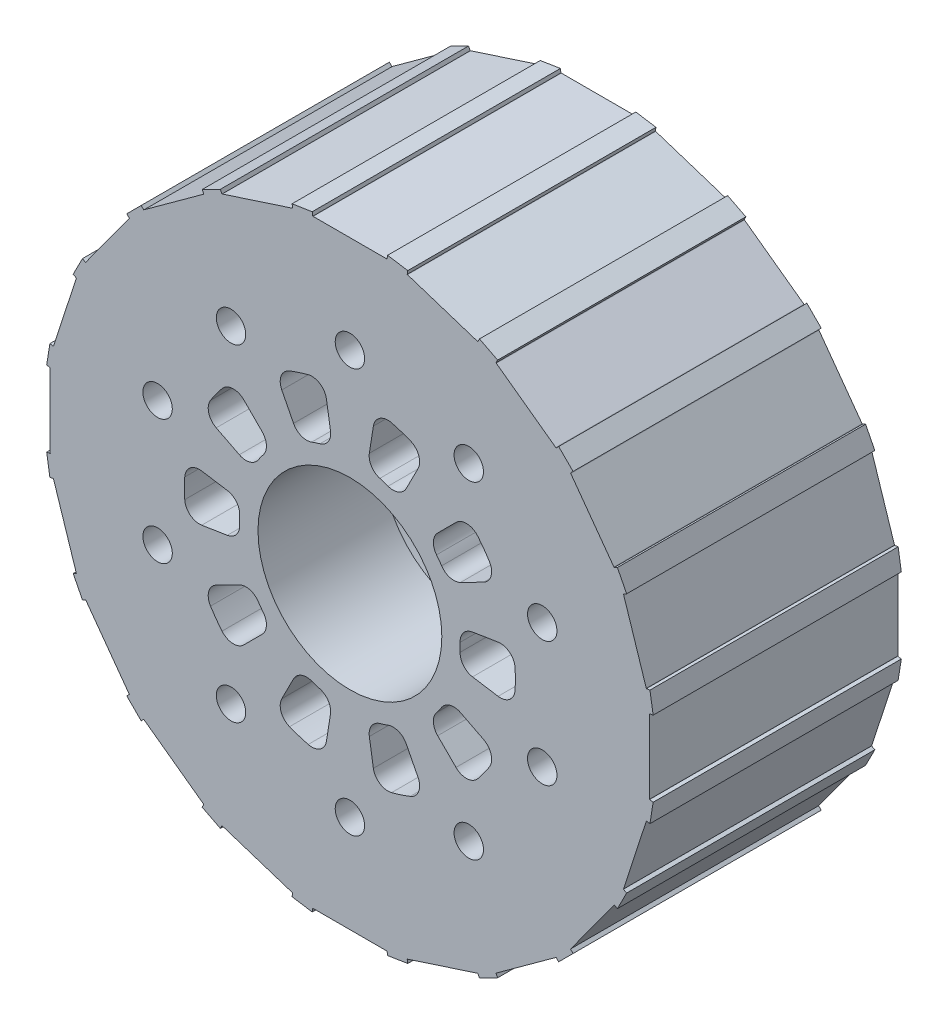
SolidWorks part; units mm, degrees
ref_plane "Ön Düzlem" through (0, 0, 0) normal (0, 0, 1) x (1, 0, 0)
ref_plane "Üst Düzlem" through (0, 0, 0) normal (0, 1, 0) x (1, 0, 0)
ref_plane "Sağ Düzlem" through (0, 0, 0) normal (1, 0, 0) x (0, 0, -1)
sketch "Sketch1" plane through (0, 0, 0) normal (0, 0, 1) x (1, 0, 0)
  line L0 (0, 0) -> (0, 81.5)
  line L1 (10, 81.5) -> (-10, 81.5)
  line L2 (-10, 81.5) -> (-10, 87.5)
  line L3 (10, 81.5) -> (10, 87.5)
  line L4 (15.6743, 80.6013) -> (17.5284, 86.3076)
  line L5 (34.6955, 74.4209) -> (36.5496, 80.1273)
  line L6 (34.6955, 74.4209) -> (15.6743, 80.6013)
  line L7 (39.8143, 71.8127) -> (43.341, 76.6668)
  line L8 (55.9947, 60.057) -> (59.5214, 64.9111)
  line L9 (55.9947, 60.057) -> (39.8143, 71.8127)
  line L10 (60.057, 55.9947) -> (64.9111, 59.5214)
  line L11 (71.8127, 39.8143) -> (76.6668, 43.341)
  line L12 (71.8127, 39.8143) -> (60.057, 55.9947)
  line L13 (74.4209, 34.6955) -> (80.1273, 36.5496)
  line L14 (80.6013, 15.6743) -> (86.3076, 17.5284)
  line L15 (80.6013, 15.6743) -> (74.4209, 34.6955)
  line L16 (81.5, 10) -> (87.5, 10)
  line L17 (81.5, -10) -> (87.5, -10)
  line L18 (81.5, -10) -> (81.5, 10)
  line L19 (80.6013, -15.6743) -> (86.3076, -17.5284)
  line L20 (74.4209, -34.6955) -> (80.1273, -36.5496)
  line L21 (74.4209, -34.6955) -> (80.6013, -15.6743)
  line L22 (71.8127, -39.8143) -> (76.6668, -43.341)
  line L23 (60.057, -55.9947) -> (64.9111, -59.5214)
  line L24 (60.057, -55.9947) -> (71.8127, -39.8143)
  line L25 (55.9947, -60.057) -> (59.5214, -64.9111)
  line L26 (39.8143, -71.8127) -> (43.341, -76.6668)
  line L27 (39.8143, -71.8127) -> (55.9947, -60.057)
  line L28 (34.6955, -74.4209) -> (36.5496, -80.1273)
  line L29 (15.6743, -80.6013) -> (17.5284, -86.3076)
  line L30 (15.6743, -80.6013) -> (34.6955, -74.4209)
  line L31 (10, -81.5) -> (10, -87.5)
  line L32 (-10, -81.5) -> (-10, -87.5)
  line L33 (-10, -81.5) -> (10, -81.5)
  line L34 (-15.6743, -80.6013) -> (-17.5284, -86.3076)
  line L35 (-34.6955, -74.4209) -> (-36.5496, -80.1273)
  line L36 (-34.6955, -74.4209) -> (-15.6743, -80.6013)
  line L37 (-39.8143, -71.8127) -> (-43.341, -76.6668)
  line L38 (-55.9947, -60.057) -> (-59.5214, -64.9111)
  line L39 (-55.9947, -60.057) -> (-39.8143, -71.8127)
  line L40 (-60.057, -55.9947) -> (-64.9111, -59.5214)
  line L41 (-71.8127, -39.8143) -> (-76.6668, -43.341)
  line L42 (-71.8127, -39.8143) -> (-60.057, -55.9947)
  line L43 (-74.4209, -34.6955) -> (-80.1273, -36.5496)
  line L44 (-80.6013, -15.6743) -> (-86.3076, -17.5284)
  line L45 (-80.6013, -15.6743) -> (-74.4209, -34.6955)
  line L46 (-81.5, -10) -> (-87.5, -10)
  line L47 (-81.5, 10) -> (-87.5, 10)
  line L48 (-81.5, 10) -> (-81.5, -10)
  line L49 (-80.6013, 15.6743) -> (-86.3076, 17.5284)
  line L50 (-74.4209, 34.6955) -> (-80.1273, 36.5496)
  line L51 (-74.4209, 34.6955) -> (-80.6013, 15.6743)
  line L52 (-71.8127, 39.8143) -> (-76.6668, 43.341)
  line L53 (-60.057, 55.9947) -> (-64.9111, 59.5214)
  line L54 (-60.057, 55.9947) -> (-71.8127, 39.8143)
  line L55 (-55.9947, 60.057) -> (-59.5214, 64.9111)
  line L56 (-39.8143, 71.8127) -> (-43.341, 76.6668)
  line L57 (-39.8143, 71.8127) -> (-55.9947, 60.057)
  line L58 (-34.6955, 74.4209) -> (-36.5496, 80.1273)
  line L59 (-15.6743, 80.6013) -> (-17.5284, 86.3076)
  line L60 (-15.6743, 80.6013) -> (-34.6955, 74.4209)
  line L61 (34.6955, 74.4209) -> (34.7846, 74.3755)
  line L62 (35.1494, 75.3119) -> (40.2683, 72.7037) construction
  line L63 (39.7252, 71.8581) -> (39.8143, 71.8127)
  line L64 (35.2385, 75.2665) -> (40.1792, 72.7491)
  line L65 (34.7846, 74.3755) -> (35.2385, 75.2665)
  line L66 (55.9947, 60.057) -> (56.0654, 59.9863)
  line L67 (39.7252, 71.8581) -> (40.1792, 72.7491)
  line L68 (34.7846, 74.3755) -> (35.1931, 75.1774) construction
  line L69 (39.7252, 71.8581) -> (40.1338, 72.66) construction
  line L70 (35.1931, 75.1774) -> (40.1338, 72.66) construction
  line L71 (34.6955, 74.4209) -> (35.1494, 75.3119) construction
  line L72 (39.8143, 71.8127) -> (40.2683, 72.7037) construction
  line L73 (56.0654, 59.9863) -> (56.7725, 60.6934)
  line L74 (56.7725, 60.6934) -> (60.6934, 56.7725)
  line L75 (59.9863, 56.0654) -> (60.6934, 56.7725)
  line L76 (59.9863, 56.0654) -> (60.057, 55.9947)
  line L77 (71.8127, 39.8143) -> (71.8581, 39.7252)
  line L78 (71.8581, 39.7252) -> (72.7491, 40.1792)
  line L79 (72.7491, 40.1792) -> (75.2665, 35.2385)
  line L80 (74.3755, 34.7846) -> (75.2665, 35.2385)
  line L81 (74.3755, 34.7846) -> (74.4209, 34.6955)
  line L82 (80.6013, 15.6743) -> (80.6169, 15.5756)
  line L83 (80.6169, 15.5756) -> (81.6046, 15.732)
  line L84 (81.6046, 15.732) -> (82.472, 10.2552)
  line L85 (81.4844, 10.0988) -> (82.472, 10.2552)
  line L86 (81.4844, 10.0988) -> (81.5, 10)
  line L87 (81.5, -10) -> (81.4844, -10.0988)
  line L88 (81.4844, -10.0988) -> (82.472, -10.2552)
  line L89 (82.472, -10.2552) -> (81.6046, -15.732)
  line L90 (80.6169, -15.5756) -> (81.6046, -15.732)
  line L91 (80.6169, -15.5756) -> (80.6013, -15.6743)
  line L92 (74.4209, -34.6955) -> (74.3755, -34.7846)
  line L93 (74.3755, -34.7846) -> (75.2665, -35.2385)
  line L94 (75.2665, -35.2385) -> (72.7491, -40.1792)
  line L95 (71.8581, -39.7252) -> (72.7491, -40.1792)
  line L96 (71.8581, -39.7252) -> (71.8127, -39.8143)
  line L97 (60.057, -55.9947) -> (59.9863, -56.0654)
  line L98 (59.9863, -56.0654) -> (60.6934, -56.7725)
  line L99 (60.6934, -56.7725) -> (56.7725, -60.6934)
  line L100 (56.0654, -59.9863) -> (56.7725, -60.6934)
  line L101 (56.0654, -59.9863) -> (55.9947, -60.057)
  line L102 (39.8143, -71.8127) -> (39.7252, -71.8581)
  line L103 (39.7252, -71.8581) -> (40.1792, -72.7491)
  line L104 (40.1792, -72.7491) -> (35.2385, -75.2665)
  line L105 (34.7846, -74.3755) -> (35.2385, -75.2665)
  line L106 (34.7846, -74.3755) -> (34.6955, -74.4209)
  line L107 (15.6743, -80.6013) -> (15.5756, -80.6169)
  line L108 (15.5756, -80.6169) -> (15.732, -81.6046)
  line L109 (15.732, -81.6046) -> (10.2552, -82.472)
  line L110 (10.0988, -81.4844) -> (10.2552, -82.472)
  line L111 (10.0988, -81.4844) -> (10, -81.5)
  line L112 (-10, -81.5) -> (-10.0988, -81.4844)
  line L113 (-10.0988, -81.4844) -> (-10.2552, -82.472)
  line L114 (-10.2552, -82.472) -> (-15.732, -81.6046)
  line L115 (-15.5756, -80.6169) -> (-15.732, -81.6046)
  line L116 (-15.5756, -80.6169) -> (-15.6743, -80.6013)
  line L117 (-34.6955, -74.4209) -> (-34.7846, -74.3755)
  line L118 (-34.7846, -74.3755) -> (-35.2385, -75.2665)
  line L119 (-35.2385, -75.2665) -> (-40.1792, -72.7491)
  line L120 (-39.7252, -71.8581) -> (-40.1792, -72.7491)
  line L121 (-39.7252, -71.8581) -> (-39.8143, -71.8127)
  line L122 (-55.9947, -60.057) -> (-56.0654, -59.9863)
  line L123 (-56.0654, -59.9863) -> (-56.7725, -60.6934)
  line L124 (-56.7725, -60.6934) -> (-60.6934, -56.7725)
  line L125 (-59.9863, -56.0654) -> (-60.6934, -56.7725)
  line L126 (-59.9863, -56.0654) -> (-60.057, -55.9947)
  line L127 (-71.8127, -39.8143) -> (-71.8581, -39.7252)
  line L128 (-71.8581, -39.7252) -> (-72.7491, -40.1792)
  line L129 (-72.7491, -40.1792) -> (-75.2665, -35.2385)
  line L130 (-74.3755, -34.7846) -> (-75.2665, -35.2385)
  line L131 (-74.3755, -34.7846) -> (-74.4209, -34.6955)
  line L132 (-80.6013, -15.6743) -> (-80.6169, -15.5756)
  line L133 (-80.6169, -15.5756) -> (-81.6046, -15.732)
  line L134 (-81.6046, -15.732) -> (-82.472, -10.2552)
  line L135 (-81.4844, -10.0988) -> (-82.472, -10.2552)
  line L136 (-81.4844, -10.0988) -> (-81.5, -10)
  line L137 (-81.5, 10) -> (-81.4844, 10.0988)
  line L138 (-81.4844, 10.0988) -> (-82.472, 10.2552)
  line L139 (-82.472, 10.2552) -> (-81.6046, 15.732)
  line L140 (-80.6169, 15.5756) -> (-81.6046, 15.732)
  line L141 (-80.6169, 15.5756) -> (-80.6013, 15.6743)
  line L142 (-74.4209, 34.6955) -> (-74.3755, 34.7846)
  line L143 (-74.3755, 34.7846) -> (-75.2665, 35.2385)
  line L144 (-75.2665, 35.2385) -> (-72.7491, 40.1792)
  line L145 (-71.8581, 39.7252) -> (-72.7491, 40.1792)
  line L146 (-71.8581, 39.7252) -> (-71.8127, 39.8143)
  line L147 (-60.057, 55.9947) -> (-59.9863, 56.0654)
  line L148 (-59.9863, 56.0654) -> (-60.6934, 56.7725)
  line L149 (-60.6934, 56.7725) -> (-56.7725, 60.6934)
  line L150 (-56.0654, 59.9863) -> (-56.7725, 60.6934)
  line L151 (-56.0654, 59.9863) -> (-55.9947, 60.057)
  line L152 (-39.8143, 71.8127) -> (-39.7252, 71.8581)
  line L153 (-39.7252, 71.8581) -> (-40.1792, 72.7491)
  line L154 (-40.1792, 72.7491) -> (-35.2385, 75.2665)
  line L155 (-34.7846, 74.3755) -> (-35.2385, 75.2665)
  line L156 (-34.7846, 74.3755) -> (-34.6955, 74.4209)
  line L157 (-15.6743, 80.6013) -> (-15.5756, 80.6169)
  line L158 (-15.5756, 80.6169) -> (-15.732, 81.6046)
  line L159 (-15.732, 81.6046) -> (-10.2552, 82.472)
  line L160 (-10.0988, 81.4844) -> (-10.2552, 82.472)
  line L161 (-10.0988, 81.4844) -> (-10, 81.5)
  line L162 (10, 81.5) -> (10.0988, 81.4844)
  line L163 (10.0988, 81.4844) -> (10.2552, 82.472)
  line L164 (10.2552, 82.472) -> (15.732, 81.6046)
  line L165 (15.5756, 80.6169) -> (15.732, 81.6046)
  line L166 (15.5756, 80.6169) -> (15.6743, 80.6013)
  circle A0 centre (0, 0) radius 25
  arc A2 (10, 87.5) -> (-10, 87.5) centre (0, 38) ccw
  arc A3 (36.5496, 80.1273) -> (17.5284, 86.3076) centre (11.7426, 36.1401) ccw
  arc A4 (59.5214, 64.9111) -> (43.341, 76.6668) centre (22.3358, 30.7426) ccw
  arc A5 (76.6668, 43.341) -> (64.9111, 59.5214) centre (30.7426, 22.3358) ccw
  arc A6 (86.3076, 17.5284) -> (80.1273, 36.5496) centre (36.1401, 11.7426) ccw
  arc A7 (87.5, -10) -> (87.5, 10) centre (38, 0) ccw
  arc A8 (80.1273, -36.5496) -> (86.3076, -17.5284) centre (36.1401, -11.7426) ccw
  arc A9 (64.9111, -59.5214) -> (76.6668, -43.341) centre (30.7426, -22.3358) ccw
  arc A10 (43.341, -76.6668) -> (59.5214, -64.9111) centre (22.3358, -30.7426) ccw
  arc A11 (17.5284, -86.3076) -> (36.5496, -80.1273) centre (11.7426, -36.1401) ccw
  arc A12 (-10, -87.5) -> (10, -87.5) centre (0, -38) ccw
  arc A13 (-36.5496, -80.1273) -> (-17.5284, -86.3076) centre (-11.7426, -36.1401) ccw
  arc A14 (-59.5214, -64.9111) -> (-43.341, -76.6668) centre (-22.3358, -30.7426) ccw
  arc A15 (-76.6668, -43.341) -> (-64.9111, -59.5214) centre (-30.7426, -22.3358) ccw
  arc A16 (-86.3076, -17.5284) -> (-80.1273, -36.5496) centre (-36.1401, -11.7426) ccw
  arc A17 (-87.5, 10) -> (-87.5, -10) centre (-38, 0) ccw
  arc A18 (-80.1273, 36.5496) -> (-86.3076, 17.5284) centre (-36.1401, 11.7426) ccw
  arc A19 (-64.9111, 59.5214) -> (-76.6668, 43.341) centre (-30.7426, 22.3358) ccw
  arc A20 (-43.341, 76.6668) -> (-59.5214, 64.9111) centre (-22.3358, 30.7426) ccw
  arc A21 (-17.5284, 86.3076) -> (-36.5496, 80.1273) centre (-11.7426, 36.1401) ccw
  point P7 (0, 81.5)
  point P107 (0, 0)
  point P231 (0, 0)
  dimension "D1" = 81.5
  dimension "D3" = 50.5
  dimension "D8" = 50
  dimension "D2" = 20
  dimension "D4" = 6
  dimension "D5" = 6
  dimension "D7" = 20
  dimension "D6" = 20
extrude "Boss-Extrude1" add sketch "Sketch1" along normal blind 67.5
sketch "Sketch2" plane through (0, 0, 0) normal (0, 0, -1) x (-1, 0, 0)
  circle A0 centre (0, 0) radius 68
extrude "Cut-Extrude1" cut sketch "Sketch2" against normal blind 33.75
sketch "Sketch3" plane through (0, 0, 33.75) normal (0, 0, -1) x (-1, 0, 0)
  line L0 (0, 0) -> (0, 55)
  circle A0 centre (0, 55) radius 4
  circle A1 centre (32.3282, 44.4959) radius 4
  circle A2 centre (52.3081, 16.9959) radius 4
  circle A3 centre (52.3081, -16.9959) radius 4
  circle A4 centre (32.3282, -44.4959) radius 4
  circle A5 centre (0, -55) radius 4
  circle A6 centre (-32.3282, -44.4959) radius 4
  circle A7 centre (-52.3081, -16.9959) radius 4
  circle A8 centre (-52.3081, 16.9959) radius 4
  circle A9 centre (-32.3282, 44.4959) radius 4
  point P5 (0, 0)
  point P24 (0, 0)
  dimension "D1" = 10
extrude "Cut-Extrude2" cut sketch "Sketch3" against normal blind 33.75 contours A0 | A9 | A8 | A1 | A2 | A3 | A4 | A5 | A6 | A7
sketch "Sketch4" plane through (0, 0, 33.75) normal (0, 0, -1) x (-1, 0, 0)
  line L1 (-5.2818, 33.3482) -> (-6.3832, 40.302)
  line L2 (-15.3285, 30.0838) -> (-18.5248, 36.357)
  line L3 (15.3285, 30.0838) -> (18.5248, 36.357)
  line L4 (5.2818, 33.3482) -> (6.3832, 40.302)
  line L5 (30.0838, 15.3285) -> (36.357, 18.5248)
  line L6 (23.8747, 23.8747) -> (28.8531, 28.8531)
  line L7 (33.3482, -5.2818) -> (40.302, -6.3832)
  line L8 (33.3482, 5.2818) -> (40.302, 6.3832)
  line L9 (23.8747, -23.8747) -> (28.8531, -28.8531)
  line L10 (30.0838, -15.3285) -> (36.357, -18.5248)
  line L11 (5.2818, -33.3482) -> (6.3832, -40.302)
  line L12 (15.3285, -30.0838) -> (18.5248, -36.357)
  line L13 (-15.3285, -30.0838) -> (-18.5248, -36.357)
  line L14 (-5.2818, -33.3482) -> (-6.3832, -40.302)
  line L18 (-30.0838, 15.3285) -> (-36.357, 18.5248)
  line L19 (-23.8747, 23.8747) -> (-28.8531, 28.8531)
  line L24 (-30.0838, -15.3285) -> (-36.357, -18.5248)
  line L25 (-23.8747, -23.8747) -> (-28.8531, -28.8531)
  line L26 (-33.3482, 5.2818) -> (-40.302, 6.3832)
  line L27 (-33.3482, -5.2818) -> (-40.302, -6.3832)
  arc A0 (-34.7724, 28.5636) -> (-37.9109, 24.2439) centre (0, 0) ccw
  arc A1 (-23.5616, 18.5702) -> (-24.9422, 16.6699) centre (0, 0) ccw
  arc A6 (-37.9109, 24.2439) -> (-36.357, 18.5248) centre (-34.541, 22.0888) ccw
  arc A7 (-30.0838, 15.3285) -> (-24.9422, 16.6699) centre (-28.2679, 18.8925) ccw
  arc A8 (-23.5616, 18.5702) -> (-23.8747, 23.8747) centre (-26.7031, 21.0462) ccw
  arc A9 (-28.8531, 28.8531) -> (-34.7724, 28.5636) centre (-31.6815, 26.0246) ccw
  arc A10 (-6.3832, 40.302) -> (-11.3422, 43.5472) centre (-10.334, 39.6763) ccw
  arc A11 (-8.1464, 28.8728) -> (-5.2818, 33.3482) centre (-9.2326, 32.7225) ccw
  arc A12 (-11.3422, 43.5472) -> (-16.4204, 41.8971) centre (0, 0) ccw
  arc A13 (-16.4204, 41.8971) -> (-18.5248, 36.357) centre (-14.9608, 38.173) ccw
  arc A14 (-15.3285, 30.0838) -> (-10.3804, 28.1469) centre (-11.7645, 31.8998) ccw
  arc A15 (-8.1464, 28.8728) -> (-10.3804, 28.1469) centre (0, 0) ccw
  arc A16 (18.5248, 36.357) -> (16.4204, 41.8971) centre (14.9608, 38.173) ccw
  arc A17 (10.3804, 28.1469) -> (15.3285, 30.0838) centre (11.7645, 31.8998) ccw
  arc A18 (16.4204, 41.8971) -> (11.3422, 43.5472) centre (0, 0) ccw
  arc A19 (11.3422, 43.5472) -> (6.3832, 40.302) centre (10.334, 39.6763) ccw
  arc A20 (5.2818, 33.3482) -> (8.1464, 28.8728) centre (9.2326, 32.7225) ccw
  arc A21 (10.3804, 28.1469) -> (8.1464, 28.8728) centre (0, 0) ccw
  arc A22 (36.357, 18.5248) -> (37.9109, 24.2439) centre (34.541, 22.0888) ccw
  arc A23 (24.9422, 16.6699) -> (30.0838, 15.3285) centre (28.2679, 18.8925) ccw
  arc A24 (37.9109, 24.2439) -> (34.7724, 28.5636) centre (0, 0) ccw
  arc A25 (34.7724, 28.5636) -> (28.8531, 28.8531) centre (31.6815, 26.0246) ccw
  arc A26 (23.8747, 23.8747) -> (23.5616, 18.5702) centre (26.7031, 21.0462) ccw
  arc A27 (24.9422, 16.6699) -> (23.5616, 18.5702) centre (0, 0) ccw
  arc A28 (40.302, -6.3832) -> (44.9207, -2.6698) centre (40.9278, -2.4325) ccw
  arc A29 (29.977, -1.1745) -> (33.3482, -5.2818) centre (33.9739, -1.3311) ccw
  arc A30 (44.9207, -2.6698) -> (44.9207, 2.6698) centre (0, 0) ccw
  arc A31 (44.9207, 2.6698) -> (40.302, 6.3832) centre (40.9278, 2.4325) ccw
  arc A32 (33.3482, 5.2818) -> (29.977, 1.1745) centre (33.9739, 1.3311) ccw
  arc A33 (29.977, -1.1745) -> (29.977, 1.1745) centre (0, 0) ccw
  arc A34 (28.8531, -28.8531) -> (34.7724, -28.5636) centre (31.6815, -26.0246) ccw
  arc A35 (23.5616, -18.5702) -> (23.8747, -23.8747) centre (26.7031, -21.0462) ccw
  arc A36 (34.7724, -28.5636) -> (37.9109, -24.2439) centre (0, 0) ccw
  arc A37 (37.9109, -24.2439) -> (36.357, -18.5248) centre (34.541, -22.0888) ccw
  arc A38 (30.0838, -15.3285) -> (24.9422, -16.6699) centre (28.2679, -18.8925) ccw
  arc A39 (23.5616, -18.5702) -> (24.9422, -16.6699) centre (0, 0) ccw
  arc A40 (6.3832, -40.302) -> (11.3422, -43.5472) centre (10.334, -39.6763) ccw
  arc A41 (8.1464, -28.8728) -> (5.2818, -33.3482) centre (9.2326, -32.7225) ccw
  arc A42 (11.3422, -43.5472) -> (16.4204, -41.8971) centre (0, 0) ccw
  arc A43 (16.4204, -41.8971) -> (18.5248, -36.357) centre (14.9608, -38.173) ccw
  arc A44 (15.3285, -30.0838) -> (10.3804, -28.1469) centre (11.7645, -31.8998) ccw
  arc A45 (8.1464, -28.8728) -> (10.3804, -28.1469) centre (0, 0) ccw
  arc A46 (-18.5248, -36.357) -> (-16.4204, -41.8971) centre (-14.9608, -38.173) ccw
  arc A47 (-10.3804, -28.1469) -> (-15.3285, -30.0838) centre (-11.7645, -31.8998) ccw
  arc A48 (-16.4204, -41.8971) -> (-11.3422, -43.5472) centre (0, 0) ccw
  arc A49 (-11.3422, -43.5472) -> (-6.3832, -40.302) centre (-10.334, -39.6763) ccw
  arc A50 (-5.2818, -33.3482) -> (-8.1464, -28.8728) centre (-9.2326, -32.7225) ccw
  arc A51 (-10.3804, -28.1469) -> (-8.1464, -28.8728) centre (0, 0) ccw
  arc A52 (-36.357, -18.5248) -> (-37.9109, -24.2439) centre (-34.541, -22.0888) ccw
  arc A53 (-24.9422, -16.6699) -> (-30.0838, -15.3285) centre (-28.2679, -18.8925) ccw
  arc A54 (-37.9109, -24.2439) -> (-34.7724, -28.5636) centre (0, 0) ccw
  arc A55 (-34.7724, -28.5636) -> (-28.8531, -28.8531) centre (-31.6815, -26.0246) ccw
  arc A56 (-23.8747, -23.8747) -> (-23.5616, -18.5702) centre (-26.7031, -21.0462) ccw
  arc A57 (-24.9422, -16.6699) -> (-23.5616, -18.5702) centre (0, 0) ccw
  arc A58 (-40.302, 6.3832) -> (-44.9207, 2.6698) centre (-40.9278, 2.4325) ccw
  arc A59 (-29.977, 1.1745) -> (-33.3482, 5.2818) centre (-33.9739, 1.3311) ccw
  arc A60 (-44.9207, 2.6698) -> (-44.9207, -2.6698) centre (0, 0) ccw
  arc A61 (-44.9207, -2.6698) -> (-40.302, -6.3832) centre (-40.9278, -2.4325) ccw
  arc A62 (-33.3482, -5.2818) -> (-29.977, -1.1745) centre (-33.9739, -1.3311) ccw
  arc A63 (-29.977, 1.1745) -> (-29.977, -1.1745) centre (0, 0) ccw
  point P132 (0, 0)
  dimension "D1" = 4
extrude "Cut-Extrude3" cut sketch "Sketch4" against normal blind 33.75
